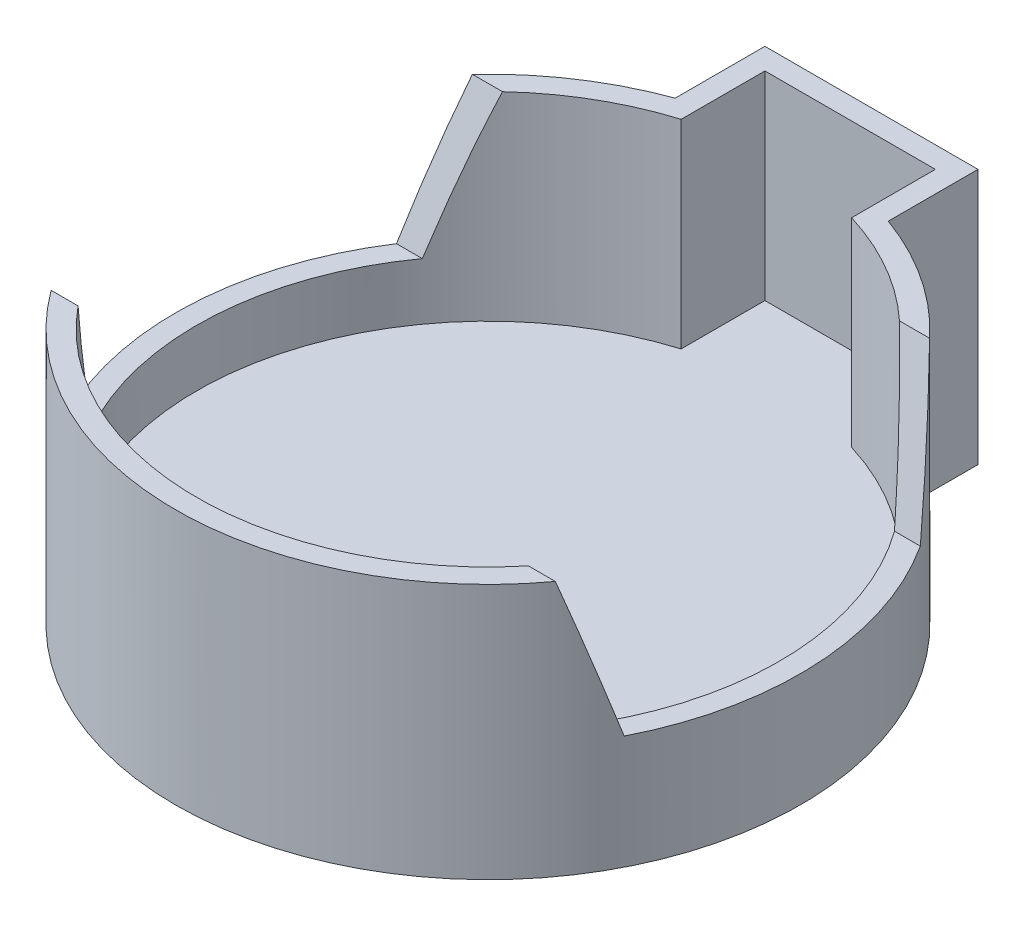
SolidWorks part; units mm, degrees
ref_plane "前视基准面" through (0, 0, 0) normal (0, 0, 1) x (1, 0, 0)
ref_plane "上视基准面" through (0, 0, 0) normal (0, 1, 0) x (1, 0, 0)
ref_plane "右视基准面" through (0, 0, 0) normal (1, 0, 0) x (0, 0, -1)
sketch "草图1" plane through (0, 0, 0) normal (0, 1, 0) x (1, 0, 0)
  line L0 (0, 34.8049) -> (0, -44.2857) construction
  line L1 (-3.75, 10.3411) -> (-3.75, 13.5)
  line L2 (-3.75, 13.5) -> (3.75, 13.5)
  line L3 (3.75, 10.3411) -> (3.75, 13.5)
  line L4 (-16.9631, -11) -> (30.96, -11) construction
  arc A0 (3.75, 10.3411) -> (-3.75, 10.3411) centre (0, 0) cw
  point P9 (0, 13.5)
  dimension "D1" = 11
  dimension "D2" = 7.5
  dimension "D3" = 24.5
extrude "凸台-拉伸1" add sketch "草图1" along normal blind 9
shell "抽壳1" thickness 0.75
sketch "草图2" plane through (0, 0, 0) normal (1, 0, 0) x (0, 0, -1)
  line L0 (-6.5, 9) -> (-5, 4)
  line L1 (10.3411, 9) -> (-11, 9) construction
  line L2 (-5, 4) -> (6, 4)
  line L3 (6, 4) -> (7.5, 9)
  line L4 (-11, 0) -> (10.3411, 0) construction
  line L6 (-11, 9) -> (-11, 0) construction
  line L7 (0.5, -3.5467) -> (0.5, 14.8146) construction
  line L8 (-6.5, 9) -> (7.5, 9)
  dimension "D1" = 11
  dimension "D2" = 14
  dimension "D3" = 4
  dimension "D4" = 6
extrude "切除-拉伸1" cut sketch "草图2" against normal through all and the other way through all
